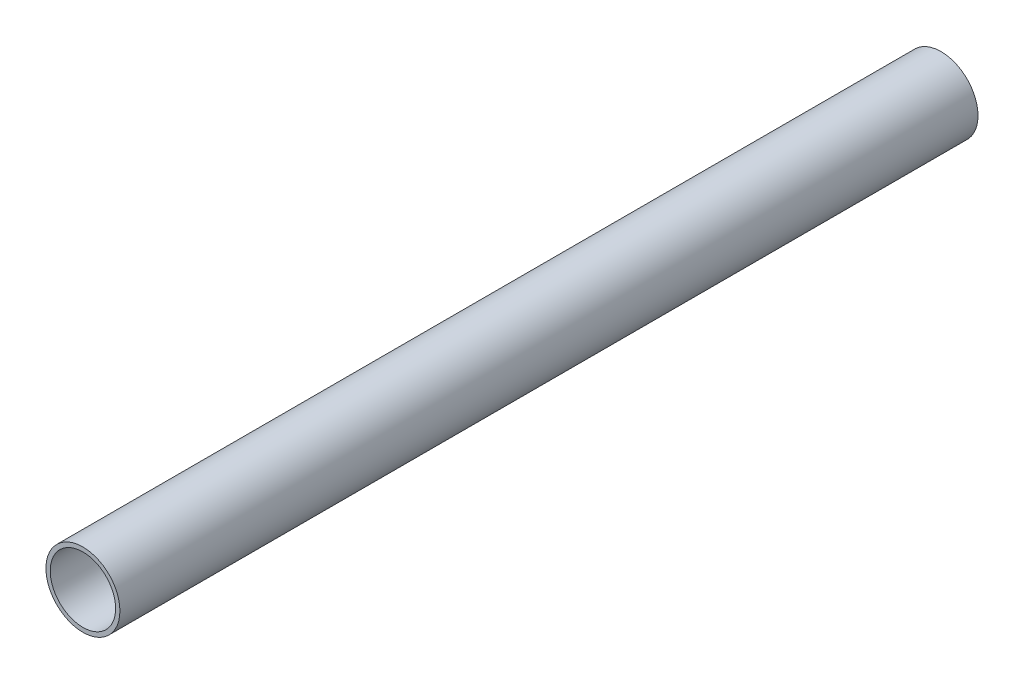
SolidWorks part; units mm, degrees
ref_plane "Alzado" through (0, 0, 0) normal (0, 0, 1) x (1, 0, 0)
ref_plane "Planta" through (0, 0, 0) normal (0, 1, 0) x (1, 0, 0)
ref_plane "Vista lateral" through (0, 0, 0) normal (1, 0, 0) x (0, 0, -1)
sketch "Croquis1" plane through (0, 0, 0) normal (0, 0, 1) x (1, 0, 0)
  circle A0 centre (0, 0) radius 86.2
  circle A1 centre (0, 0) radius 76.2
  dimension "D1" = 152.4
  dimension "D2" = 10
extrude "Saliente-Extruir1" add sketch "Croquis1" against normal blind 2000
